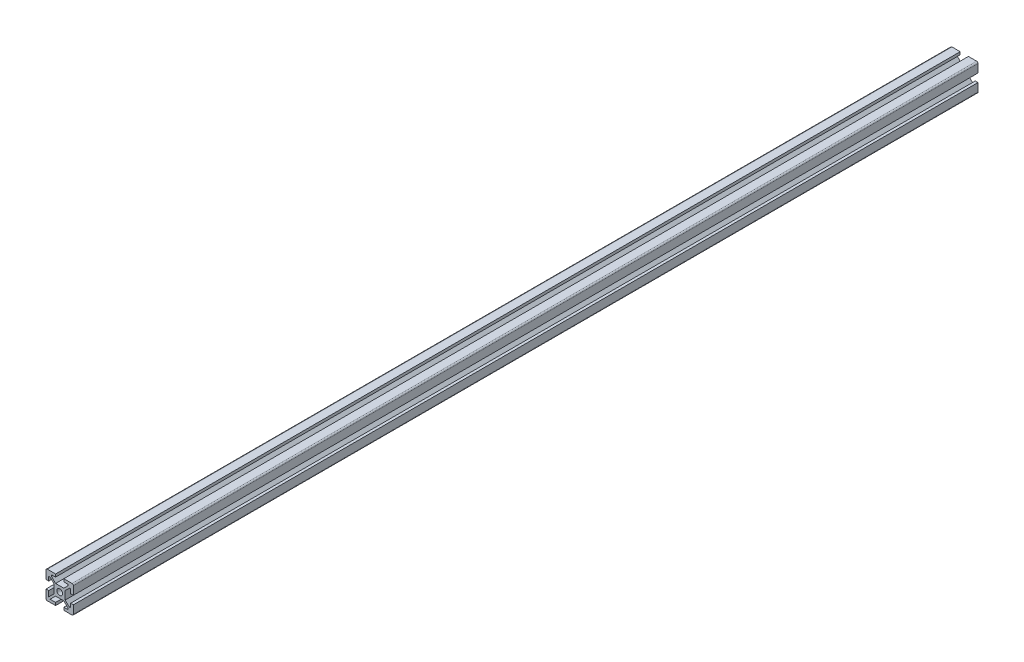
SolidWorks part; units mm, degrees
ref_plane "Front Plane" through (0, 0, 0) normal (0, 0, 1) x (1, 0, 0)
ref_plane "Top Plane" through (0, 0, 0) normal (0, 1, 0) x (1, 0, 0)
ref_plane "Right Plane" through (0, 0, 0) normal (1, 0, 0) x (0, 0, -1)
sketch "Sketch1" plane through (0, 0, 0) normal (0, 0, 1) x (1, 0, 0)
  line L0 (0, 10) -> (0, -10) construction
  line L1 (10, 10) -> (-10, 10)
  line L2 (10, 10) -> (10, -10)
  line L3 (10, -10) -> (-10, -10)
  line L4 (-10, 10) -> (-10, -10)
  line L5 (10, 10) -> (-10, -10) construction
  line L6 (10, -10) -> (-10, 10) construction
  line L7 (-10, 0) -> (10, 0) construction
  line L8 (-4, 3) -> (-8, 7)
  line L9 (6, 6) -> (-6, 6)
  line L10 (6, 6) -> (6, -6)
  line L11 (6, -6) -> (-6, -6)
  line L12 (-6, 6) -> (-6, -6)
  line L13 (6, 6) -> (-6, -6) construction
  line L14 (6, -6) -> (-6, 6) construction
  line L15 (4, 4) -> (-4, 4)
  line L16 (4, 4) -> (4, -4)
  line L17 (4, -4) -> (-4, -4)
  line L18 (-4, 4) -> (-4, -4)
  line L19 (4, 4) -> (-4, -4) construction
  line L20 (4, -4) -> (-4, 4) construction
  line L21 (3, 10) -> (-3, 10)
  line L22 (3, 10) -> (3, -10)
  line L23 (3, -10) -> (-3, -10)
  line L24 (-3, 10) -> (-3, -10)
  line L25 (3, 10) -> (-3, -10) construction
  line L26 (3, -10) -> (-3, 10) construction
  line L27 (10, 3) -> (-10, 3)
  line L28 (10, 3) -> (10, -3)
  line L29 (10, -3) -> (-10, -3)
  line L30 (-10, 3) -> (-10, -3)
  line L31 (10, 3) -> (-10, -3) construction
  line L32 (10, -3) -> (-10, 3) construction
  line L33 (8, 8) -> (-8, 8)
  line L34 (8, 8) -> (8, -8)
  line L35 (8, -8) -> (-8, -8)
  line L36 (-8, 8) -> (-8, -8)
  line L37 (8, 8) -> (-8, -8) construction
  line L38 (8, -8) -> (-8, 8) construction
  line L39 (-3, 4) -> (-7, 8)
  line L40 (3, 4) -> (7, 8)
  line L41 (4, 3) -> (8, 7)
  line L42 (-4, -3) -> (-8, -7)
  line L43 (-3, -4) -> (-7, -8)
  line L44 (3, -4) -> (7, -8)
  line L45 (4, -3) -> (8, -7)
  line L46 (-6, 6) -> (-6, 8)
  line L47 (-6, 6) -> (-8, 6)
  line L48 (-6, -6) -> (-8, -6)
  line L49 (-6, -6) -> (-6, -8)
  line L50 (6, -6) -> (6, -8)
  line L51 (6, -6) -> (8, -6)
  line L52 (6, 6) -> (6, 8)
  line L53 (6, 6) -> (8, 6)
  circle A0 centre (0, 0) radius 2.1
  point P0 (0, 0)
  point P10 (0, 0)
  point P15 (0, 0)
  point P20 (0, 0)
  point P25 (0, 0)
  point P30 (0, 0)
  dimension "D11" = 4.2
  dimension "D1" = 20
  dimension "D2" = 20
  dimension "D3" = 12
  dimension "D4" = 12
  dimension "D5" = 8
  dimension "D6" = 8
  dimension "D7" = 6
  dimension "D8" = 6
  dimension "D9" = 2
  dimension "D10" = 2
extrude "Boss-Extrude1" add sketch "Sketch1" along normal blind 660.4 contours L39 L46 L33 | L47 L46 L39 L33 L36 L8 | L47 L8 L36 | L36 L33 L24 L1 L4 L27 | L12 L47 L8 | L46 L9 L39 | L15 L39 L9 L12 L8 L18 | L27 L24 L15 L18 | L27 L22 L15 L24 | L29 L24 L27 L18 | L29 L22 L27 L24 A0 | L27 L16 L15 L22 | L16 L41 L10 L9 L40 L15 | L9 L52 L40 | L53 L10 L41 | L52 L53 L41 L34 L33 L40 | L52 L40 L33 | L41 L53 L34 | L33 L34 L27 L2 L1 L22 | L29 L16 L27 L22 | L16 L29 L22 L17 | L45 L16 L17 L44 L11 L10 | L10 L51 L45 | L50 L11 L44 | L51 L50 L44 L35 L34 L45 | L44 L50 L35 | L51 L45 L34 | L34 L35 L22 L3 L2 L29 | L22 L29 L24 L17 | L24 L29 L18 L17 | L43 L17 L18 L42 L12 L11 | L11 L49 L43 | L48 L12 L42 | L49 L48 L42 L36 L35 L43 | L36 L29 L4 L3 L24 L35
fillet "Fillet1" radius 1 4 edges at (-10, 10, 330.2) (-10, -10, 330.2) (10, -10, 330.2) (10, 10, 330.2)
